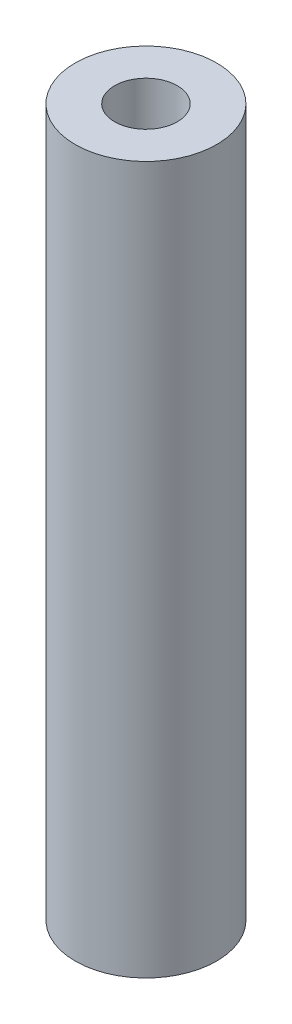
SolidWorks part; units mm, degrees
material "尼龙 6/10"
ref_plane "前视基准面" through (0, 0, 0) normal (0, 0, 1) x (1, 0, 0)
ref_plane "上视基准面" through (0, 0, 0) normal (0, 1, 0) x (1, 0, 0)
ref_plane "右视基准面" through (0, 0, 0) normal (1, 0, 0) x (0, 0, -1)
sketch "草图2" plane through (0, 0, 0) normal (0, 1, 0) x (1, 0, 0)
  circle A0 centre (0, 0) radius 1.55
  circle A1 centre (0, 0) radius 3.5
  dimension "D1" = 3.1
  dimension "D2" = 7
extrude "凸台-拉伸1" add sketch "草图2" along normal blind 35
